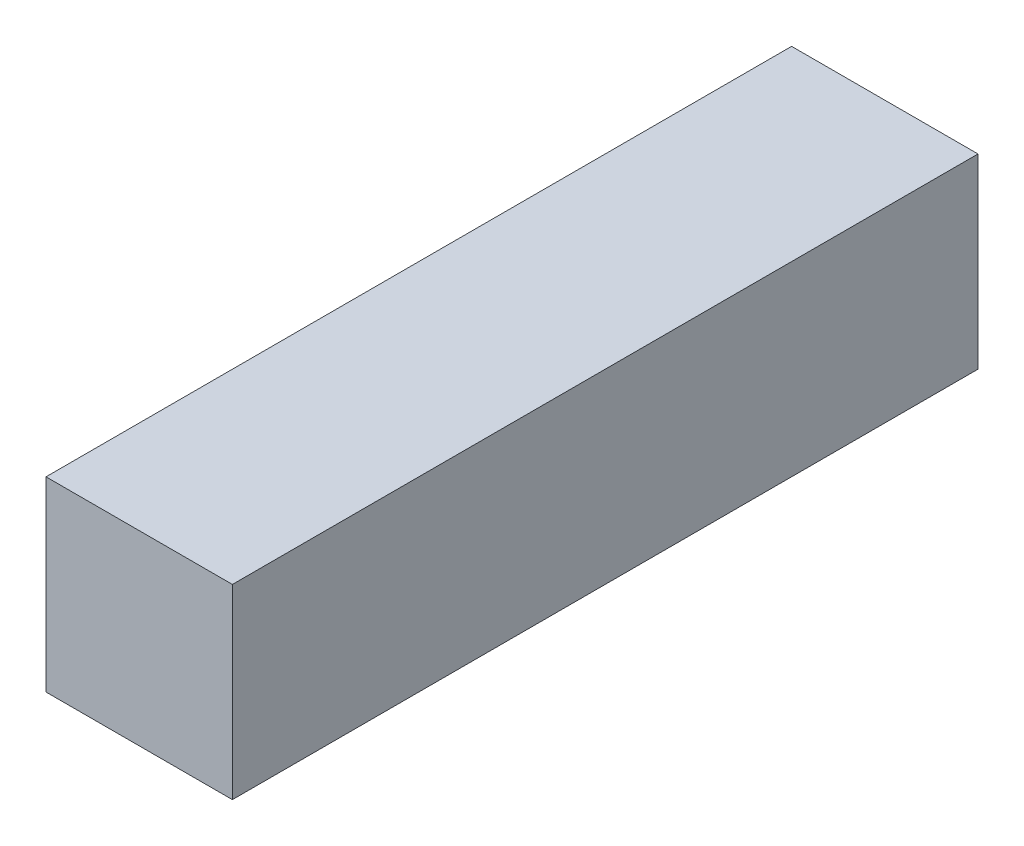
SolidWorks part; units mm, degrees
material "Plain Carbon Steel"
ref_plane "Front Plane" through (0, 0, 0) normal (0, 0, 1) x (1, 0, 0)
ref_plane "Top Plane" through (0, 0, 0) normal (0, 1, 0) x (1, 0, 0)
ref_plane "Right Plane" through (0, 0, 0) normal (1, 0, 0) x (0, 0, -1)
sketch "Sketch1" plane through (0, 0, 0) normal (0, 0, 1) x (1, 0, 0)
  line L1 (-3.175, -3.175) -> (3.175, -3.175)
  line L2 (-3.175, -3.175) -> (-3.175, 3.175)
  line L3 (-3.175, 3.175) -> (3.175, 3.175)
  line L4 (3.175, -3.175) -> (3.175, 3.175)
  line L5 (-3.175, -3.175) -> (3.175, 3.175) construction
  line L6 (-3.175, 3.175) -> (3.175, -3.175) construction
  point P0 (0, 0)
  dimension "D1" = 6.35
  dimension "D2" = 6.35
extrude "Boss-Extrude1" add sketch "Sketch1" along normal mid plane 25.4
